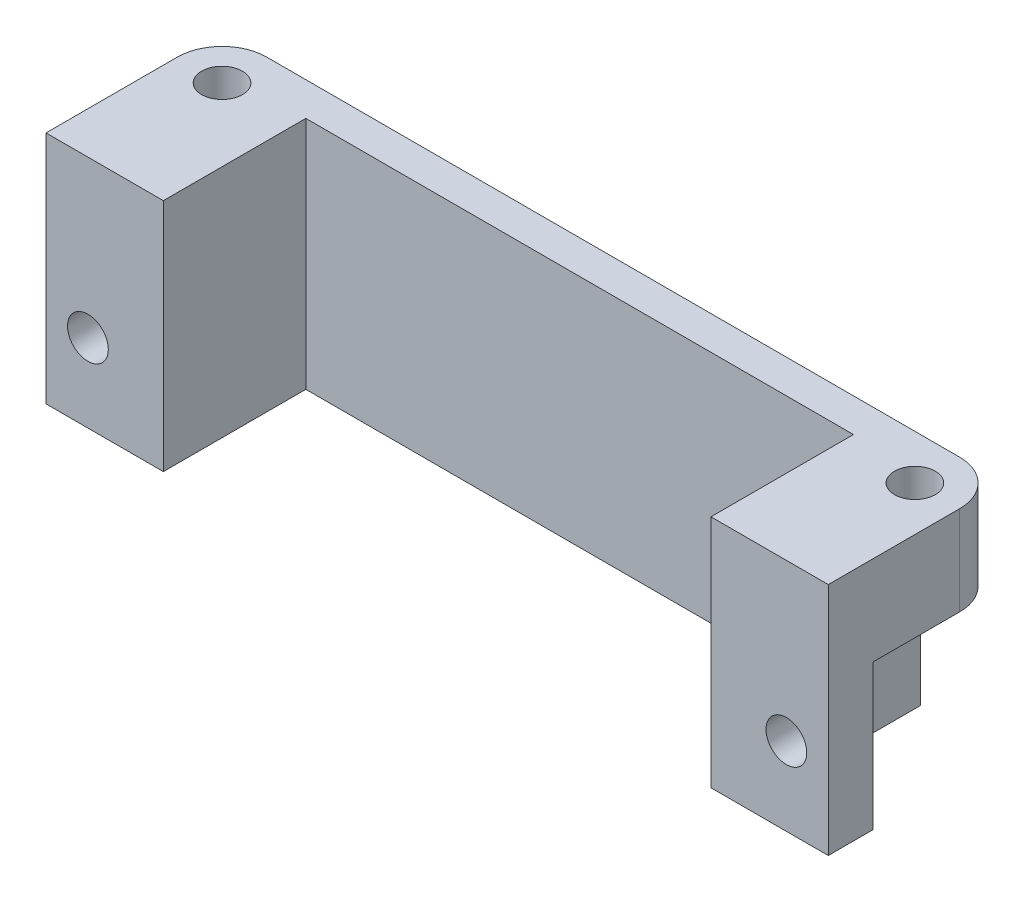
SolidWorks part; units mm, degrees
ref_plane "Front Plane" through (0, 0, 0) normal (0, 0, 1) x (1, 0, 0)
ref_plane "Top Plane" through (0, 0, 0) normal (0, 1, 0) x (1, 0, 0)
ref_plane "Right Plane" through (0, 0, 0) normal (1, 0, 0) x (0, 0, -1)
sketch "Sketch1" plane through (0, 0, 0) normal (0, 1, 0) x (1, 0, 0)
  line L0 (0, -12.75) -> (0, 12.75) construction
  line L1 (-24.5, -12.75) -> (24.5, -12.75)
  line L2 (-24.5, -12.75) -> (-24.5, 12.75)
  line L3 (-24.5, 12.75) -> (24.5, 12.75)
  line L4 (24.5, -12.75) -> (24.5, 12.75)
  line L5 (-24.5, -12.75) -> (24.5, 12.75) construction
  line L6 (-24.5, 12.75) -> (24.5, -12.75) construction
  line L7 (0, 12.75) -> (0, 15.75)
  line L9 (0, 15.75) -> (-27.5, 15.75)
  line L10 (0, 15.75) -> (0, 12.75)
  line L11 (0, 12.75) -> (-27.5, 12.75)
  line L12 (-27.5, 15.75) -> (-27.5, 12.75)
  line L13 (-24.5, 12.75) -> (-27.5, 12.75)
  line L14 (-24.5, 12.75) -> (-24.5, 0)
  line L15 (-24.5, 0) -> (-27.5, 0)
  line L16 (-27.5, 12.75) -> (-27.5, 0)
  line L17 (-27.5, 0) -> (-35, 0)
  line L18 (-27.5, 0) -> (-27.5, 3)
  line L19 (-27.5, 3) -> (-35, 3)
  line L20 (-35, 0) -> (-35, 3)
  line L21 (-35, 3) -> (-27.5, 3)
  line L22 (-35, 3) -> (-35, 15.75)
  line L23 (-35, 15.75) -> (-27.5, 15.75)
  line L24 (-27.5, 3) -> (-27.5, 15.75)
  point P0 (0, 0)
  dimension "D1" = 49
  dimension "D2" = 25.5
  dimension "D3" = 3
  dimension "D4" = 27.5
  dimension "D5" = 12.75
  dimension "D6" = 7.5
  dimension "D7" = 3
extrude "Boss-Extrude1" add sketch "Sketch1" along normal blind 21
sketch "Sketch2" plane through (0, 0, 0) normal (0, 0, 1) x (1, 0, 0)
  line L0 (-27.5, 0) -> (-27.5, 21) construction
  line L1 (-24.5, 0) -> (-35, 0) construction
  line L2 (-24.5, 21) -> (-35, 21) construction
  line L3 (-24.5, 21) -> (-24.5, 0) construction
  line L4 (-27.5, 14) -> (-35, 14)
  line L5 (-35, 21) -> (-35, 0) construction
  line L6 (-35, 14) -> (-27.5, 0) construction
  line L7 (-27.5, 0) -> (-35, 0) construction
  line L8 (-35, 0) -> (-27.5, 14) construction
  circle A0 centre (-31.25, 7) radius 1.825
  dimension "D3" = 3.65
  dimension "D1" = 3
  dimension "D2" = 7
extrude "Cut-Extrude1" cut sketch "Sketch2" against normal blind 4 contours A0
sketch "Sketch3" plane through (0, 0, 0) normal (0, -1, 0) x (1, 0, 0)
  line L0 (-24.5, 0) -> (-24.5, -12.75) construction
  line L1 (-35, -15.75) -> (-27.5, -15.75)
  line L2 (-35, -15.75) -> (-35, -4)
  line L3 (-35, -4) -> (-27.5, -4)
  line L4 (-27.5, -15.75) -> (-27.5, -4)
  line L5 (-24.5, 0) -> (-35, 0) construction
  dimension "D1" = 3
  dimension "D2" = 4
extrude "Cut-Extrude2" cut sketch "Sketch3" against normal blind 13
fillet "Fillet1" radius 4 1 edges at (-35, 17, -15.75)
sketch "Sketch5" plane through (0, 13, 0) normal (0, -1, 0) x (1, 0, 0)
  line L0 (-35, -11.75) -> (-27.5, -11.75) construction
  line L1 (-27.5, -15.75) -> (-27.5, -4) construction
  line L2 (-31, -15.75) -> (-31, -4) construction
  line L3 (-27.5, -4) -> (-35, -4) construction
  circle A0 centre (-31, -11.75) radius 1.825
  dimension "D1" = 3.65
extrude "Cut-Extrude3" cut sketch "Sketch5" against normal through all
mirror "Mirror1" about plane through (0, 21, 0) normal (-1, 0, 0) of "Cut-Extrude3", "Fillet1", "Cut-Extrude1", "Cut-Extrude2", "Boss-Extrude1"
